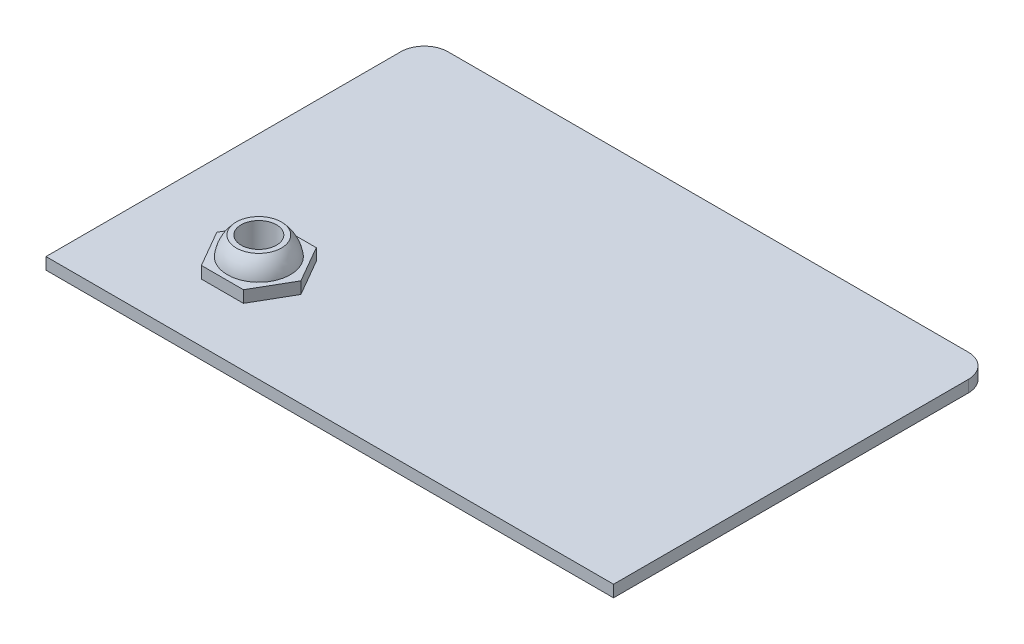
SolidWorks part; units mm, degrees
ref_plane "Front Plane" through (0, 0, 0) normal (0, 0, 1) x (1, 0, 0)
ref_plane "Top Plane" through (0, 0, 0) normal (0, 1, 0) x (1, 0, 0)
ref_plane "Right Plane" through (0, 0, 0) normal (1, 0, 0) x (0, 0, -1)
sketch "Sketch1" plane through (0, 0, 0) normal (0, 1, 0) x (1, 0, 0)
  line L1 (0, 0) -> (152.4, 0)
  line L2 (0, 0) -> (0, 95.25)
  line L3 (6.35, 101.6) -> (146.05, 101.6)
  line L4 (152.4, 0) -> (152.4, 95.25)
  arc A0 (146.05, 101.6) -> (152.4, 95.25) centre (146.05, 95.25) cw
  arc A1 (0, 95.25) -> (6.35, 101.6) centre (6.35, 95.25) cw
  point P5 (31.75, 25.4)
  point P8 (152.4, 101.6)
  point P11 (152.4, 0)
  dimension "D5" = 6.35
  dimension "D6" = 6.35
  dimension "D1" = 152.4
  dimension "D2" = 101.6
  dimension "D3" = 31.75
  dimension "D4" = 25.4
extrude "Extrude1" add sketch "Sketch1" against normal blind 3.175
sketch "Sketch2" plane through (0, 0, 0) normal (0, 1, 0) x (1, 0, 0)
  line L1 (43.0418, 25.4) -> (37.3959, 35.179)
  line L2 (37.3959, 35.179) -> (26.1041, 35.179)
  line L3 (26.1041, 35.179) -> (20.4582, 25.4)
  line L4 (20.4582, 25.4) -> (26.1041, 15.621)
  line L5 (26.1041, 15.621) -> (37.3959, 15.621)
  line L6 (37.3959, 15.621) -> (43.0418, 25.4)
  circle A0 centre (31.75, 25.4) radius 9.779 construction
  dimension "D3" = 19.558
  dimension "D1" = 31.75
  dimension "D2" = 25.4
extrude "Extrude2" add sketch "Sketch2" along normal blind 3.175
ref_plane "Plane1" through (0, 0, -25.4) normal (0, 0, 1) x (1, 0, 0)
sketch "Sketch3" plane through (0, 0, -25.4) normal (0, 0, 1) x (1, 0, 0)
  line L2 (31.75, 8.1916) -> (37.8116, 8.1916)
  line L4 (37.3959, 3.175) -> (43.0418, 3.175) construction
  line L5 (40.2142, 3.175) -> (31.75, 3.175)
  line L6 (26.1041, 3.175) -> (37.3959, 3.175) construction
  line L7 (31.75, 3.175) -> (31.75, 8.1916)
  arc A0 (37.8116, 8.1916) -> (40.2142, 3.175) centre (31.5475, 2.108) cw
revolve "Revolve1" add sketch "Sketch3" angle 360 about L7
ref_plane "Plane2" through (0, 8.1916, 0) normal (0, 1, 0) x (-1, 0, 0)
sketch "Sketch4" plane through (0, 8.1916, 0) normal (0, 1, 0) x (-1, 0, 0)
  circle A0 centre (-31.75, -25.4) radius 4.7507
extrude "Extrude3" cut sketch "Sketch4" against normal through all
sketch "Sketch5" plane through (0, 0, 0) normal (0, 1, 0) x (1, 0, 0)
  point P0 (19.05, 79.375)
  point P1 (127, 19.05)
  point P2 (114.3, 76.2)
  point P3 (76.2, 53.975)
  dimension "D1" = 19.05
  dimension "D2" = 79.375
  dimension "D3" = 76.2
  dimension "D4" = 53.975
  dimension "D5" = 114.3
  dimension "D6" = 76.2
  dimension "D7" = 127
  dimension "D8" = 19.05
